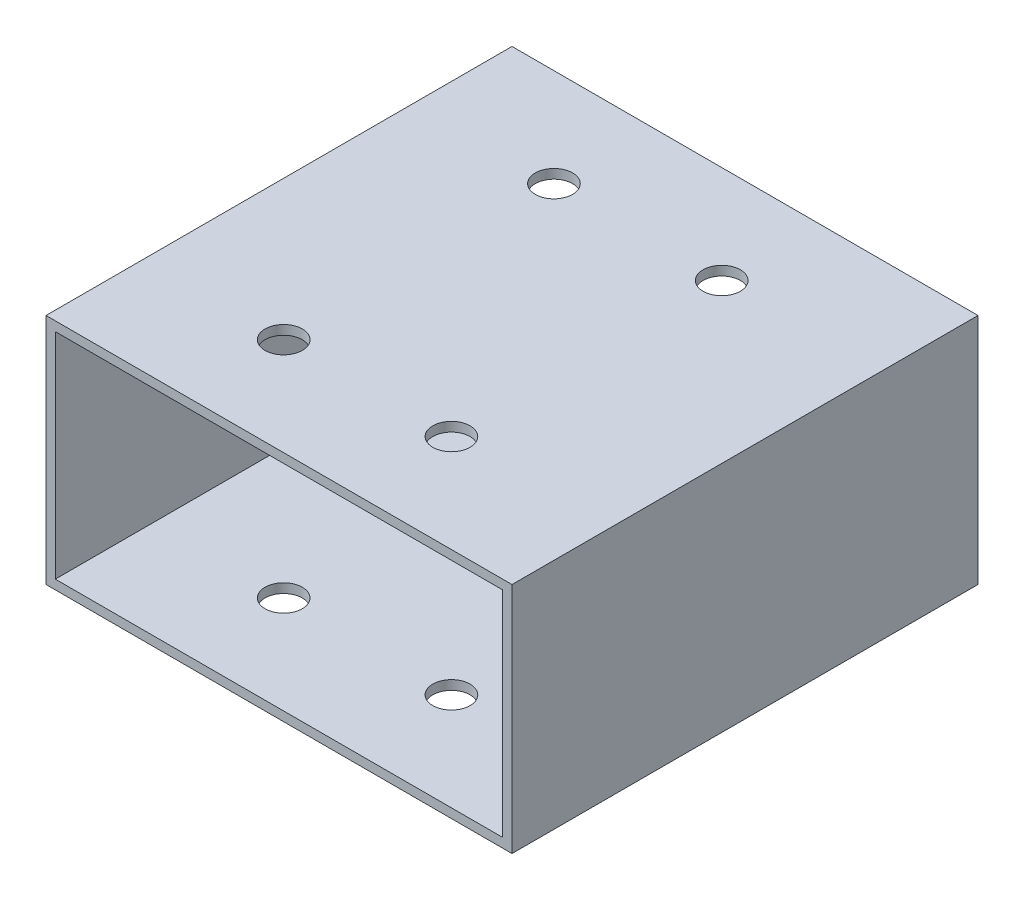
SolidWorks part; units mm, degrees
ref_plane "前视基准面" through (0, 0, 0) normal (0, 0, 1) x (1, 0, 0)
ref_plane "上视基准面" through (0, 0, 0) normal (0, 1, 0) x (1, 0, 0)
ref_plane "右视基准面" through (0, 0, 0) normal (1, 0, 0) x (0, 0, -1)
other "Configuration Table"
sketch "草图1" plane through (0, 0, 0) normal (0, 0, 1) x (1, 0, 0)
  line L1 (0, 0) -> (50, 0)
  line L2 (0, 0) -> (0, 25)
  line L3 (0, 25) -> (50, 25)
  line L4 (50, 0) -> (50, 25)
  line L5 (1, 1) -> (49, 1)
  line L6 (1, 1) -> (1, 24)
  line L7 (1, 24) -> (49, 24)
  line L8 (49, 1) -> (49, 24)
  dimension "D1" = 50
  dimension "D2" = 25
  dimension "D3" = 1
  dimension "D4" = 1
  dimension "D5" = 1
  dimension "D6" = 1
extrude "凸台-拉伸1" add sketch "草图1" along normal blind 50
sketch "草图2" plane through (0, 25, 0) normal (0, 1, 0) x (1, 0, 0)
  circle A0 centre (15, -10.5) radius 2
  circle A1 centre (15, -39.5) radius 3.1
  circle A2 centre (15, -39.5) radius 3.1 construction
  circle A3 centre (33, -39.5) radius 3.1
  circle A4 centre (33, -39.5) radius 3.1 construction
  circle A5 centre (33, -10.5) radius 3.1
  circle A6 centre (33, -10.5) radius 3.1 construction
  circle A7 centre (15, -10.5) radius 3.1
  circle A8 centre (15, -10.5) radius 3.1 construction
  circle A9 centre (33, -10.5) radius 2
  circle A10 centre (33, -39.5) radius 2
  circle A11 centre (15, -39.5) radius 2
  dimension "D5" = 4
  dimension "D1" = 0
  dimension "D2" = 0
  dimension "D3" = 0
  dimension "D4" = 0
extrude "切除-拉伸1" cut sketch "草图2" against normal blind 50
